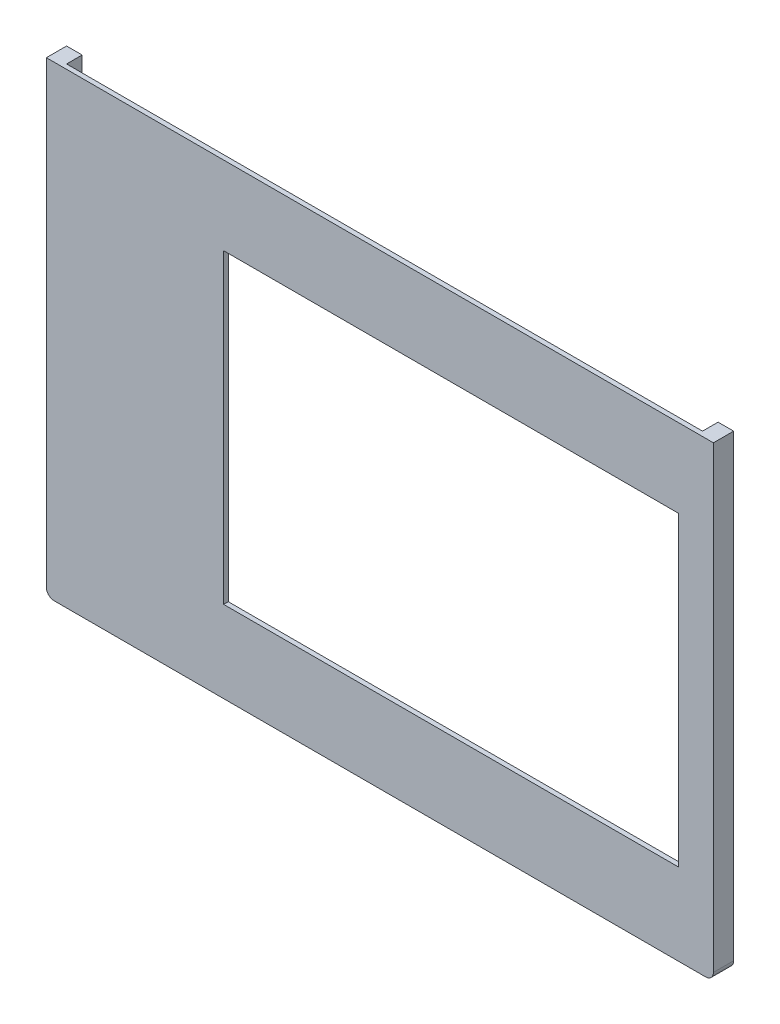
SolidWorks part; units mm, degrees
ref_plane "前视基准面" through (0, 0, 0) normal (0, 0, 1) x (1, 0, 0)
ref_plane "上视基准面" through (0, 0, 0) normal (0, 1, 0) x (1, 0, 0)
ref_plane "右视基准面" through (0, 0, 0) normal (1, 0, 0) x (0, 0, -1)
sketch "草图1" plane through (0, 0, 0) normal (0, 0, 1) x (1, 0, 0)
  line L1 (-42.9, 30) -> (42.9, 30)
  line L2 (-42.9, 30) -> (-42.9, -30)
  line L3 (-42.9, -30) -> (42.9, -30)
  line L4 (42.9, 30) -> (42.9, -30)
  line L5 (-42.9, 30) -> (42.9, -30) construction
  line L6 (-42.9, -30) -> (42.9, 30) construction
  line L7 (-20.1, 19.9) -> (38.4, 19.9)
  line L8 (-20.1, 19.9) -> (-20.1, -19.5)
  line L9 (-20.1, -19.5) -> (38.4, -19.5)
  line L10 (38.4, 19.9) -> (38.4, -19.5)
  point P0 (0, 0)
  dimension "D1" = 60
  dimension "D2" = 85.8
  dimension "D3" = 4.5
  dimension "D4" = 10.5
  dimension "D5" = 58.5
  dimension "D6" = 39.4
extrude "凸台-拉伸1" add sketch "草图1" along normal blind 0.6
sketch "草图2" plane through (0, 0, 0) normal (0, 0, -1) x (-1, 0, 0)
  line L0 (42.9, 30) -> (42.9, -30) construction
  line L1 (-42.9, -30) -> (42.9, -30)
  line L2 (-42.9, -30) -> (-42.9, -28)
  line L3 (-42.9, -28) -> (42.9, -28)
  line L4 (42.9, -30) -> (42.9, -28)
  line L5 (-42.9, 30) -> (42.9, 30) construction
  line L6 (-42.9, -30) -> (-40.9, -30)
  line L7 (-42.9, -30) -> (-42.9, 30)
  line L8 (-42.9, 30) -> (-40.9, 30)
  line L9 (-40.9, -30) -> (-40.9, 30)
  line L11 (42.9, -30) -> (40.9, -30)
  line L12 (42.9, -30) -> (42.9, 30)
  line L13 (42.9, 30) -> (40.9, 30)
  line L14 (40.9, -30) -> (40.9, 30)
  line M6 (-42.9, 30) -> (-42.9, -30)
  line M7 (-42.9, -30) -> (42.9, -30)
  line M8 (42.9, -30) -> (42.9, 30)
  line M9 (42.9, 30) -> (-42.9, 30)
  dimension "D1" = 2
  dimension "D2" = 2
  dimension "D3" = 2
extrude "凸台-拉伸2" add sketch "草图2" along normal blind 2 contours L3 L9 M9 M6 | L1 L14 L3 L9 | L9 L3 M7 M6 | L14 L3 M8 M9 | L14 L3 M7 M8
fillet "圆角1" radius 1 2 edges at (-42.9, -30, -0.7) (42.9, -30, -0.7)
